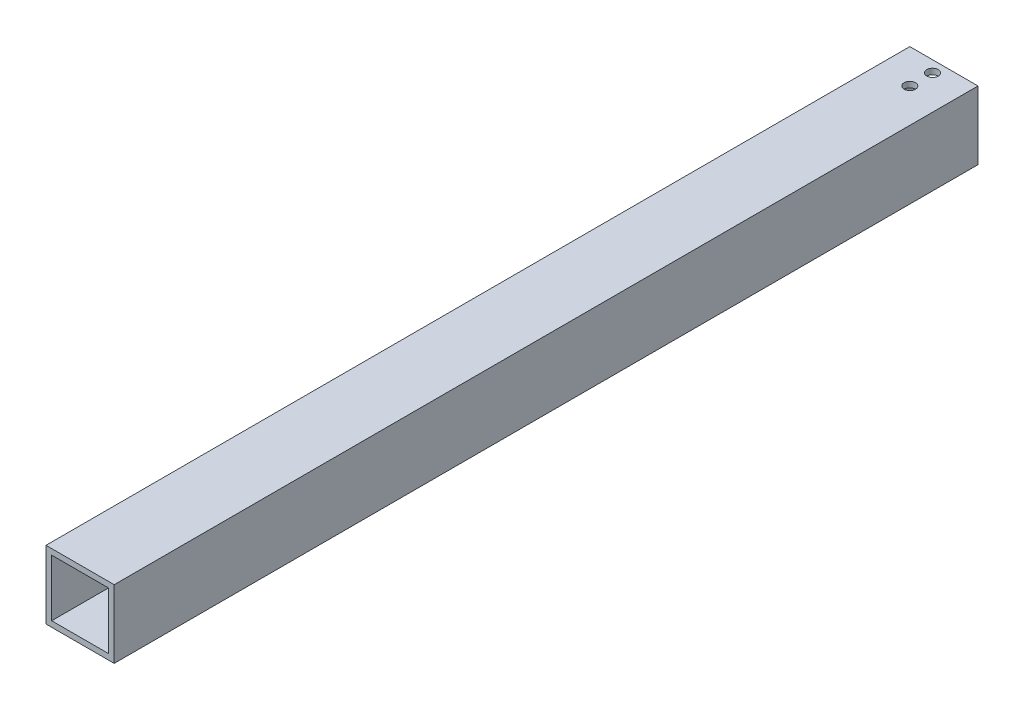
SolidWorks part; units mm, degrees
ref_plane "Front Plane" through (0, 0, 0) normal (0, 0, 1) x (1, 0, 0)
ref_plane "Top Plane" through (0, 0, 0) normal (0, 1, 0) x (1, 0, 0)
ref_plane "Right Plane" through (0, 0, 0) normal (1, 0, 0) x (0, 0, -1)
sketch "Sketch1" plane through (0, 0, 0) normal (0, 0, 1) x (1, 0, 0)
  line L1 (-19.05, 19.05) -> (19.05, 19.05)
  line L2 (-19.05, 19.05) -> (-19.05, -19.05)
  line L3 (-19.05, -19.05) -> (19.05, -19.05)
  line L4 (19.05, 19.05) -> (19.05, -19.05)
  line L5 (-19.05, 19.05) -> (19.05, -19.05) construction
  line L6 (-19.05, -19.05) -> (19.05, 19.05) construction
  line L7 (-15.875, -15.875) -> (15.875, -15.875)
  line L8 (-15.875, -15.875) -> (-15.875, 15.875)
  line L9 (-15.875, 15.875) -> (15.875, 15.875)
  line L10 (15.875, -15.875) -> (15.875, 15.875)
  line L11 (-15.875, -15.875) -> (15.875, 15.875) construction
  line L12 (-15.875, 15.875) -> (15.875, -15.875) construction
  point P0 (0, 0)
  point P6 (0, 0)
  dimension "D1" = 38.1
  dimension "D2" = 38.1
  dimension "D3" = 3.175
  dimension "D4" = 3.175
extrude "Boss-Extrude1" add sketch "Sketch1" along normal blind 482.6
sketch "Sketch2" plane through (0, 19.05, 0) normal (0, 1, 0) x (1, 0, 0)
  line L2 (-19.05, 0) -> (19.05, 0) construction
  circle A0 centre (0, -19.05) radius 3.175
  circle A1 centre (0, -6.35) radius 3.175
  point P4 (0, -423.0868)
  dimension "D1" = 6.35
  dimension "D2" = 6.35
  dimension "D3" = 6.35
  dimension "D4" = 12.7
extrude "Cut-Extrude1" cut sketch "Sketch2" against normal through all
